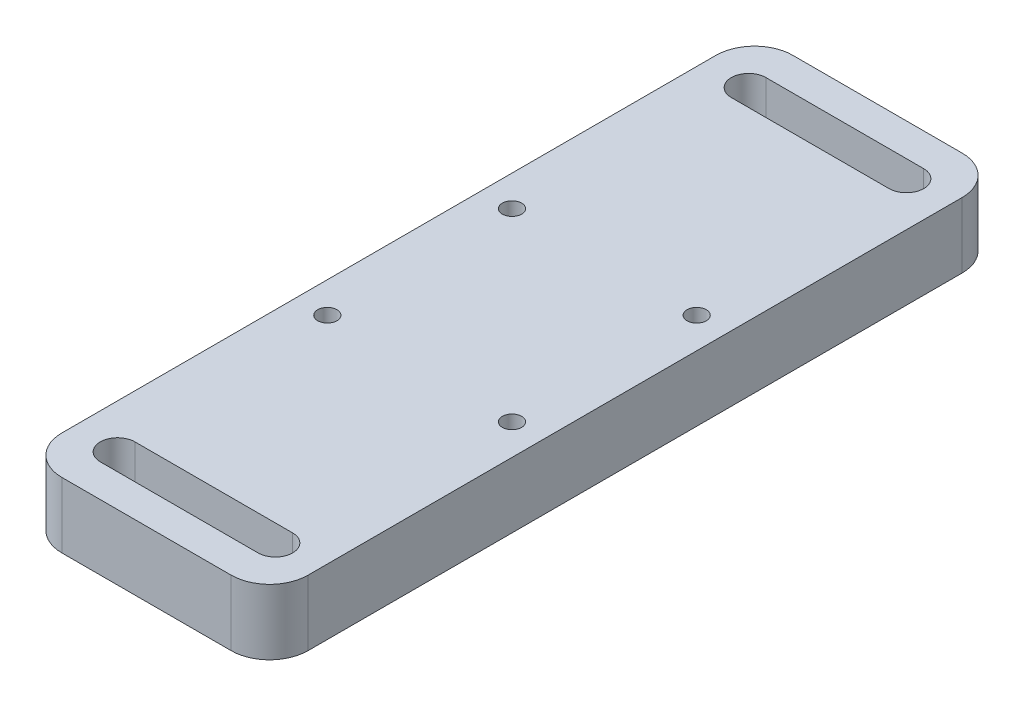
SolidWorks part; units mm, degrees
material "PBT Общее назначение"
ref_plane "Спереди" through (0, 0, 0) normal (0, 0, 1) x (1, 0, 0)
ref_plane "Сверху" through (0, 0, 0) normal (0, 1, 0) x (1, 0, 0)
ref_plane "Справа" through (0, 0, 0) normal (1, 0, 0) x (0, 0, -1)
sketch "Эскиз1" plane through (0, 0, 0) normal (0, 1, 0) x (1, 0, 0)
  line L0 (0, 0) -> (32, 0)
  line L1 (0, 0) -> (0, 35)
  line L2 (32, 0) -> (32, 35)
  line L3 (0, 35) -> (32, 35)
  dimension "D1" = 35
  dimension "D2" = 32
extrude "Бобышка-Вытянуть1" add sketch "Эскиз1" along normal blind 10.75
sketch "Эскиз2" plane through (0, 0, 0) normal (0, -1, 0) x (1, 0, 0)
  line L0 (16, 0) -> (16, -35) construction
  line L1 (0, 0) -> (32, 0) construction
  line L2 (32, -35) -> (0, -35) construction
sketch "Эскиз3" plane through (0, 0, 0) normal (0, 0, 1) x (1, 0, 0)
  line L0 (16, 0) -> (16, 10.75) construction
  line L1 (0, 10.75) -> (32, 10.75) construction
  line L2 (14.5, 0) -> (17.5, 0)
  line L3 (14.5, 0) -> (14.5, 2.25)
  line L4 (17.5, 0) -> (17.5, 2.25)
  line L5 (14.5, 2.25) -> (17.5, 2.25)
  line L6 (0, 0) -> (32, 0) construction
  line L7 (19.5, 0) -> (22.5, 0)
  line L8 (19.5, 0) -> (19.5, 2.25)
  line L9 (22.5, 0) -> (22.5, 2.25)
  line L10 (19.5, 2.25) -> (22.5, 2.25)
  line L11 (24.5, 0) -> (27.5, 0)
  line L12 (24.5, 0) -> (24.5, 2.25)
  line L13 (27.5, 0) -> (27.5, 2.25)
  line L14 (24.5, 2.25) -> (27.5, 2.25)
  line L15 (29.5, 0) -> (32.5, 0)
  line L16 (29.5, 0) -> (29.5, 2.25)
  line L17 (32.5, 0) -> (32.5, 2.25)
  line L18 (29.5, 2.25) -> (32.5, 2.25)
  line L19 (9.5, 0) -> (12.5, 0)
  line L20 (9.5, 0) -> (9.5, 2.25)
  line L21 (12.5, 0) -> (12.5, 2.25)
  line L22 (9.5, 2.25) -> (12.5, 2.25)
  line L23 (4.5, 0) -> (7.5, 0)
  line L24 (4.5, 0) -> (4.5, 2.25)
  line L25 (7.5, 0) -> (7.5, 2.25)
  line L26 (4.5, 2.25) -> (7.5, 2.25)
  line L27 (-0.5, 0) -> (2.5, 0)
  line L28 (-0.5, 0) -> (-0.5, 2.25)
  line L29 (2.5, 0) -> (2.5, 2.25)
  line L30 (-0.5, 2.25) -> (2.5, 2.25)
  dimension "D1" = 3
  dimension "D2" = 2.25
  dimension "D4" = 5
  dimension "D5" = 4
  dimension "D6" = 5
  dimension "D3" = 4
extrude "Вырез-Вытянуть1" cut sketch "Эскиз3" against normal through all
ref_plane "Плоскость1" through (16, 0, 0) normal (1, 0, 0) x (0, 0, -1)
sketch "Эскиз4" plane through (0, 10.75, 0) normal (0, 1, 0) x (1, 0, 0)
  line L0 (0, 17.5) -> (32, 17.5) construction
  line L1 (0, 35) -> (0, 0) construction
  line L2 (32, 0) -> (32, 35) construction
ref_plane "Плоскость2" through (0, 0, -17.5) normal (0, 0, 1) x (1, 0, 0)
sketch "Эскиз6" plane through (0, 0, 0) normal (0, -1, 0) x (1, 0, 0)
  line L0 (16, 0) -> (16, -35) construction
  line L1 (0, -17.5) -> (32, -17.5) construction
  line L2 (16, 0) -> (16, -35) construction
  line L3 (0, -17.5) -> (32, -17.5) construction
  circle A0 centre (16, -17.5) radius 4.5
  dimension "D1" = 9
extrude "Вырез-Вытянуть4" cut sketch "Эскиз6" against normal up to surface (2.25 mm away) up to face at (11, 2.25, -17.5)
sketch "Эскиз7" plane through (0, 10.75, 0) normal (0, 1, 0) x (1, 0, 0)
  line L2 (0, 35) -> (0, 0) construction
  line L3 (0, 0) -> (0, -25)
  line L4 (32, 0) -> (32, 35) construction
  line L5 (32, -25) -> (32, 0)
  line L6 (5, -30) -> (27, -30)
  line L7 (0, 0) -> (32, 0) construction
  line L8 (5.75, -23.5) -> (26.25, -23.5) construction
  line L9 (5.75, -21.25) -> (26.25, -21.25)
  line L10 (5.75, -25.75) -> (26.25, -25.75)
  line L11 (0, 0) -> (32, 0)
  circle A1 centre (16, -23.5) radius 2.25 construction
  arc A6 (0, -25) -> (5, -30) centre (5, -25) ccw
  arc A7 (32, -25) -> (27, -30) centre (27, -25) cw
  arc A8 (5.75, -21.25) -> (5.75, -25.75) centre (5.75, -23.5) ccw
  arc A9 (26.25, -25.75) -> (26.25, -21.25) centre (26.25, -23.5) ccw
  point P25 (16, -23.5)
  dimension "D1" = 5
  dimension "D2" = 5
  dimension "D3" = 30
  dimension "D4" = 20.5
  dimension "D5" = 4.25
  dimension "D6" = 4.5
  dimension "D7" = 16
  dimension "D8" = 10.25
extrude "Бобышка-Вытянуть2" add sketch "Эскиз7" against normal up to surface (8.5 mm away) up to face at (16, 2.25, -17.5)
mirror "Зеркальное отражение1" about plane through (0, 0, -17.5) normal (0, 0, 1) of "Бобышка-Вытянуть2"
sketch "Эскиз10" plane through (0, 10.75, 0) normal (0, 1, 0) x (1, 0, 0)
  line L0 (4, 5.5) -> (4, 29.5) construction
  line L1 (4, 5.5) -> (28, 5.5) construction
  line L2 (4, 29.5) -> (28, 29.5) construction
  line L3 (28, 5.5) -> (28, 29.5) construction
  line L4 (0, 17.5) -> (32, 17.5) construction
  line L5 (16, -30) -> (16, 65) construction
  line L6 (5, -30) -> (27, -30) construction
  line L7 (5, 65) -> (27, 65) construction
  circle A0 centre (4, 29.5) radius 1.25
  circle A1 centre (4, 5.5) radius 1.25
  circle A2 centre (28, 5.5) radius 1.25
  circle A3 centre (28, 29.5) radius 1.25
  point P0 (4, 17.5)
  point P13 (16, 29.5)
  dimension "D3" = 2.5
  dimension "D1" = 24
  dimension "D2" = 24
extrude "Вырез-Вытянуть5" cut sketch "Эскиз10" against normal through all
sketch "Эскиз11" plane through (0, 2.25, 0) normal (0, -1, 0) x (1, 0, 0)
  line L0 (28, -5.5) -> (30.3094, -5.5) construction
  line L1 (25.6906, -5.5) -> (26.8453, -7.5)
  line L2 (26.8453, -7.5) -> (29.1547, -7.5)
  line L3 (29.1547, -7.5) -> (30.3094, -5.5)
  line L4 (30.3094, -5.5) -> (29.1547, -3.5)
  line L5 (29.1547, -3.5) -> (26.8453, -3.5)
  line L6 (26.8453, -3.5) -> (25.6906, -5.5)
  line L7 (28, -29.5) -> (30.3094, -29.5) construction
  line L8 (6.3094, -5.5) -> (5.1547, -3.5)
  line L9 (5.1547, -3.5) -> (2.8453, -3.5)
  line L10 (2.8453, -3.5) -> (1.6906, -5.5)
  line L11 (1.6906, -5.5) -> (2.8453, -7.5)
  line L12 (2.8453, -7.5) -> (5.1547, -7.5)
  line L13 (5.1547, -7.5) -> (6.3094, -5.5)
  line L14 (6.3094, -29.5) -> (5.1547, -27.5)
  line L15 (5.1547, -27.5) -> (2.8453, -27.5)
  line L16 (2.8453, -27.5) -> (1.6906, -29.5)
  line L17 (1.6906, -29.5) -> (2.8453, -31.5)
  line L18 (2.8453, -31.5) -> (5.1547, -31.5)
  line L19 (5.1547, -31.5) -> (6.3094, -29.5)
  line L20 (25.6906, -29.5) -> (26.8453, -31.5)
  line L21 (26.8453, -31.5) -> (29.1547, -31.5)
  line L22 (29.1547, -31.5) -> (30.3094, -29.5)
  line L23 (30.3094, -29.5) -> (29.1547, -27.5)
  line L24 (29.1547, -27.5) -> (26.8453, -27.5)
  line L25 (26.8453, -27.5) -> (25.6906, -29.5)
  line L26 (4, -29.5) -> (6.3094, -29.5) construction
  line L27 (4, -5.5) -> (6.3094, -5.5) construction
  circle A0 centre (28, -5.5) radius 1.25 construction
  circle A1 centre (4, -5.5) radius 1.25 construction
  circle A2 centre (4, -29.5) radius 1.25 construction
  circle A3 centre (28, -29.5) radius 1.25 construction
  circle A4 centre (28, -5.5) radius 1.25 construction
  circle A5 centre (4, -5.5) radius 1.25 construction
  circle A6 centre (4, -29.5) radius 1.25 construction
  circle A7 centre (28, -29.5) radius 1.25 construction
  circle A8 centre (28, -5.5) radius 2 construction
  circle A9 centre (4, -5.5) radius 2 construction
  circle A10 centre (4, -29.5) radius 2 construction
  circle A11 centre (28, -29.5) radius 2 construction
  dimension "D1" = 4
  dimension "D2" = 4
  dimension "D3" = 4
  dimension "D4" = 4
extrude "Вырез-Вытянуть8" cut sketch "Эскиз11" against normal blind 4
sketch "Эскиз12" plane through (0, 10.75, 0) normal (0, 1, 0) x (1, 0, 0)
  line L0 (16, -21.25) -> (16, -25.75) construction
  line L1 (26.25, -21.25) -> (5.75, -21.25) construction
  line L2 (5.75, -25.75) -> (26.25, -25.75) construction
  circle A0 centre (16, -23.5) radius 12
  dimension "D1" = 24
sketch "Эскиз13" plane through (0, 0, 0) normal (0, 0, 1) x (1, 0, 0)
  line L0 (19.5, 2.25) -> (17.5, 2.25) construction
  line L1 (17.5, 2.25) -> (17.5, 0) construction
  line L2 (17.5, 0) -> (19.5, 0) construction
  line L3 (19.5, 0) -> (19.5, 2.25) construction
  line L4 (29.5, 2.25) -> (27.5, 2.25)
  line L5 (27.5, 2.25) -> (27.5, 0)
  line L6 (27.5, 0) -> (29.5, 0)
  line L7 (29.5, 0) -> (29.5, 2.25)
  line L8 (29.5, 2.25) -> (27.5, 2.25)
  line L9 (27.5, 2.25) -> (27.5, 0)
  line L10 (27.5, 0) -> (29.5, 0)
  line L11 (29.5, 0) -> (29.5, 2.25)
  line L12 (24.5, 2.25) -> (22.5, 2.25)
  line L13 (22.5, 2.25) -> (22.5, 0)
  line L14 (22.5, 0) -> (24.5, 0)
  line L15 (24.5, 0) -> (24.5, 2.25)
  line L16 (24.5, 2.25) -> (22.5, 2.25)
  line L17 (22.5, 2.25) -> (22.5, 0)
  line L18 (22.5, 0) -> (24.5, 0)
  line L19 (24.5, 0) -> (24.5, 2.25)
  line L20 (14.5, 2.25) -> (12.5, 2.25) construction
  line L21 (12.5, 2.25) -> (12.5, 0) construction
  line L22 (12.5, 0) -> (14.5, 0) construction
  line L23 (14.5, 0) -> (14.5, 2.25) construction
  line L24 (9.5, 2.25) -> (7.5, 2.25) construction
  line L25 (7.5, 2.25) -> (7.5, 0) construction
  line L26 (7.5, 0) -> (9.5, 0) construction
  line L27 (9.5, 0) -> (9.5, 2.25) construction
  line L28 (4.5, 2.25) -> (2.5, 2.25) construction
  line L29 (2.5, 2.25) -> (2.5, 0) construction
  line L30 (2.5, 0) -> (4.5, 0) construction
  line L31 (4.5, 0) -> (4.5, 2.25) construction
  line L32 (19.5, 2.25) -> (17.5, 2.25)
  line L33 (17.5, 2.25) -> (17.5, 0)
  line L34 (17.5, 0) -> (19.5, 0)
  line L35 (19.5, 0) -> (19.5, 2.25)
  line L36 (14.5, 2.25) -> (12.5, 2.25)
  line L37 (12.5, 2.25) -> (12.5, 0)
  line L38 (12.5, 0) -> (14.5, 0)
  line L39 (14.5, 0) -> (14.5, 2.25)
  line L40 (9.5, 2.25) -> (7.5, 2.25)
  line L41 (7.5, 2.25) -> (7.5, 0)
  line L42 (7.5, 0) -> (9.5, 0)
  line L43 (9.5, 0) -> (9.5, 2.25)
  line L44 (4.5, 2.25) -> (2.5, 2.25)
  line L45 (2.5, 2.25) -> (2.5, 0)
  line L46 (2.5, 0) -> (4.5, 0)
  line L47 (4.5, 0) -> (4.5, 2.25)
  dimension "D1" = 0
  dimension "D2" = 0
extrude "Бобышка-Вытянуть3" add sketch "Эскиз13" along normal blind 15
mirror "Зеркальное отражение2" about plane through (0, 0, -17.5) normal (0, 0, 1) of "Бобышка-Вытянуть3"
sketch "Эскиз14" plane through (0, 2.25, 0) normal (0, -1, 0) x (1, 0, 0)
  circle A0 centre (28, -5.5) radius 1.25 construction
  circle A1 centre (4, -5.5) radius 1.25 construction
  circle A2 centre (4, -29.5) radius 1.25 construction
  circle A3 centre (28, -29.5) radius 1.25 construction
  circle A4 centre (28, -5.5) radius 1.25 construction
  circle A5 centre (4, -5.5) radius 1.25 construction
  circle A6 centre (4, -29.5) radius 1.25 construction
  circle A7 centre (28, -29.5) radius 1.25 construction
  circle A8 centre (28, -5.5) radius 3
  circle A9 centre (28, -29.5) radius 3
  circle A10 centre (4, -29.5) radius 3
  circle A11 centre (4, -5.5) radius 3
  dimension "D1" = 6
extrude "Вырез-Вытянуть9" cut sketch "Эскиз14" along normal through all
sketch "Эскиз15" plane through (16, 0, 0) normal (1, 0, 0) x (0, 0, -1)
  line L0 (21.7426, 0) -> (21.7426, 2.25) construction
  line L1 (21.7426, 0) -> (21.7426, 2.25)
  line L2 (13.2574, 2.25) -> (13.2574, 0) construction
  line L3 (13.2574, 2.25) -> (13.2574, 0)
  line L4 (13.2574, 0) -> (21.7426, 0)
  line L5 (21.7426, 2.25) -> (13.2574, 2.25)
extrude "Вырез-Вытянуть10" cut sketch "Эскиз15" against normal through all and the other way through all
